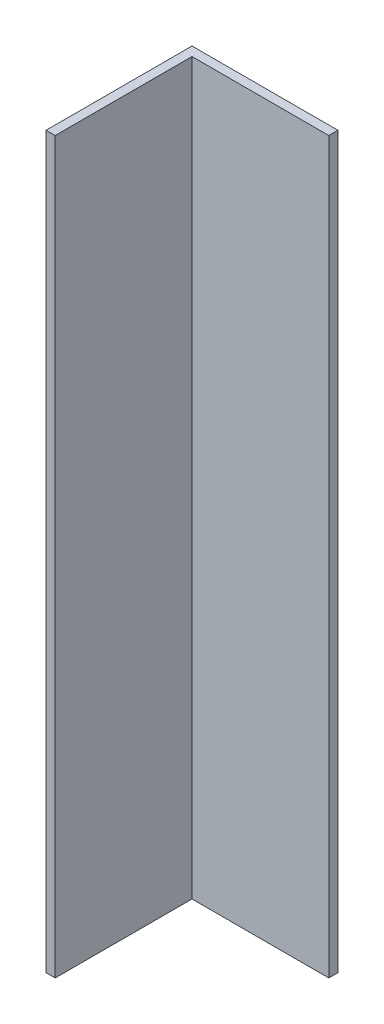
SolidWorks part; units mm, degrees
ref_plane "Front Plane" through (0, 0, 0) normal (0, 0, 1) x (1, 0, 0)
ref_plane "Top Plane" through (0, 0, 0) normal (0, 1, 0) x (1, 0, 0)
ref_plane "Right Plane" through (0, 0, 0) normal (1, 0, 0) x (0, 0, -1)
sketch "Sketch1" plane through (0, 0, 0) normal (0, 1, 0) x (1, 0, 0)
  line L1 (0, 0) -> (25.4, 0)
  line L2 (0, 0) -> (0, -25.4)
  line L3 (0, -25.4) -> (25.4, -25.4)
  line L4 (25.4, 0) -> (25.4, -25.4)
extrude "Boss-Extrude1" add sketch "Sketch1" along normal blind 127
sketch "Sketch2" plane through (0, 127, 0) normal (0, 1, 0) x (1, 0, 0)
  line L0 (25.4, -25.4) -> (25.4, 0) construction
  line L1 (25.4, -1.5875) -> (1.5875, -1.5875)
  line L2 (25.4, -1.5875) -> (25.4, -25.4)
  line L3 (25.4, -25.4) -> (1.5875, -25.4)
  line L4 (1.5875, -1.5875) -> (1.5875, -25.4)
  line L5 (0, -25.4) -> (25.4, -25.4) construction
  line L6 (25.4, 0) -> (0, 0) construction
  line L7 (0, 0) -> (0, -25.4) construction
  dimension "D1" = 1.5875
  dimension "D2" = 1.5875
extrude "Cut-Extrude1" cut sketch "Sketch2" against normal blind 127
